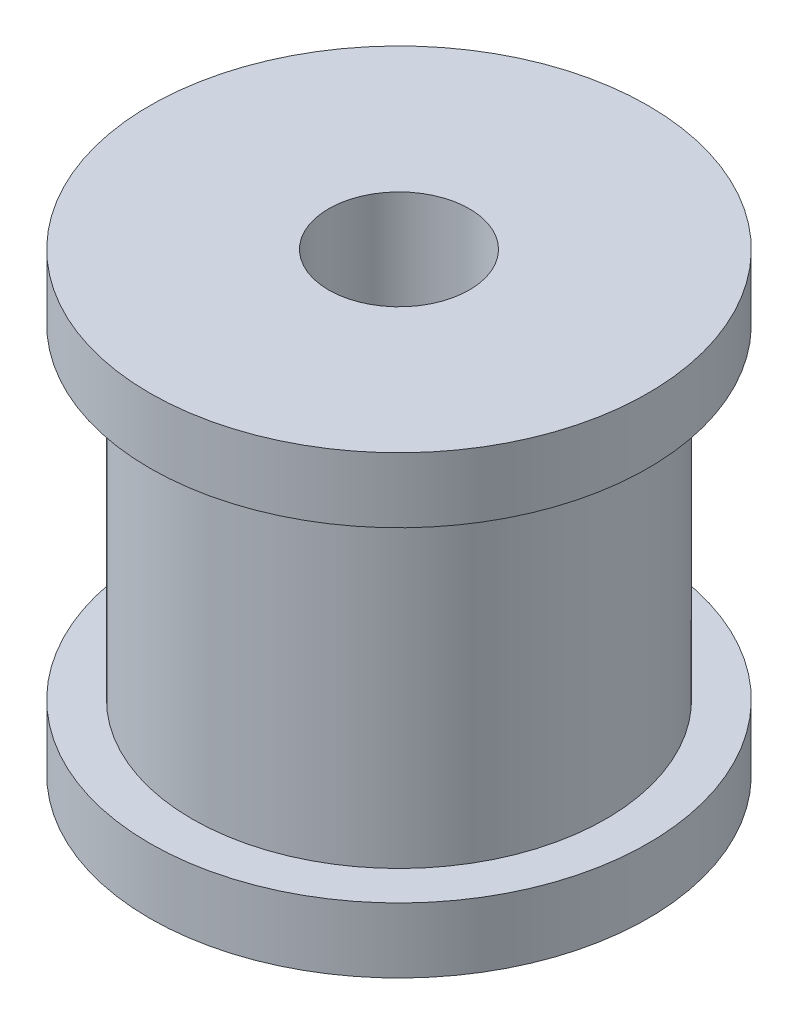
SolidWorks part; units mm, degrees
ref_plane "Front Plane" through (0, 0, 0) normal (0, 0, 1) x (1, 0, 0)
ref_plane "Top Plane" through (0, 0, 0) normal (0, 1, 0) x (1, 0, 0)
ref_plane "Right Plane" through (0, 0, 0) normal (1, 0, 0) x (0, 0, -1)
sketch "Sketch1" plane through (0, 0, 0) normal (0, 1, 0) x (1, 0, 0)
  circle A0 centre (0, 0) radius 11.5
  circle A1 centre (0, 0) radius 3.25
  dimension "D1" = 6.5
  dimension "D2" = 23
extrude "Boss-Extrude1" add sketch "Sketch1" along normal blind 3
sketch "Sketch2" plane through (0, 3, 0) normal (0, 1, 0) x (1, 0, 0)
  circle A0 centre (0, 0) radius 3.25
  circle A1 centre (0, 0) radius 9.55
  dimension "D1" = 6.5
  dimension "D2" = 19.1
extrude "Boss-Extrude2" add sketch "Sketch2" along normal blind 15
sketch "Sketch3" plane through (0, 18, 0) normal (0, 1, 0) x (1, 0, 0)
  circle A0 centre (0, 0) radius 3.25
  circle A1 centre (0, 0) radius 11.5
  dimension "D1" = 6.5
  dimension "D2" = 23
extrude "Boss-Extrude3" add sketch "Sketch3" along normal blind 3
